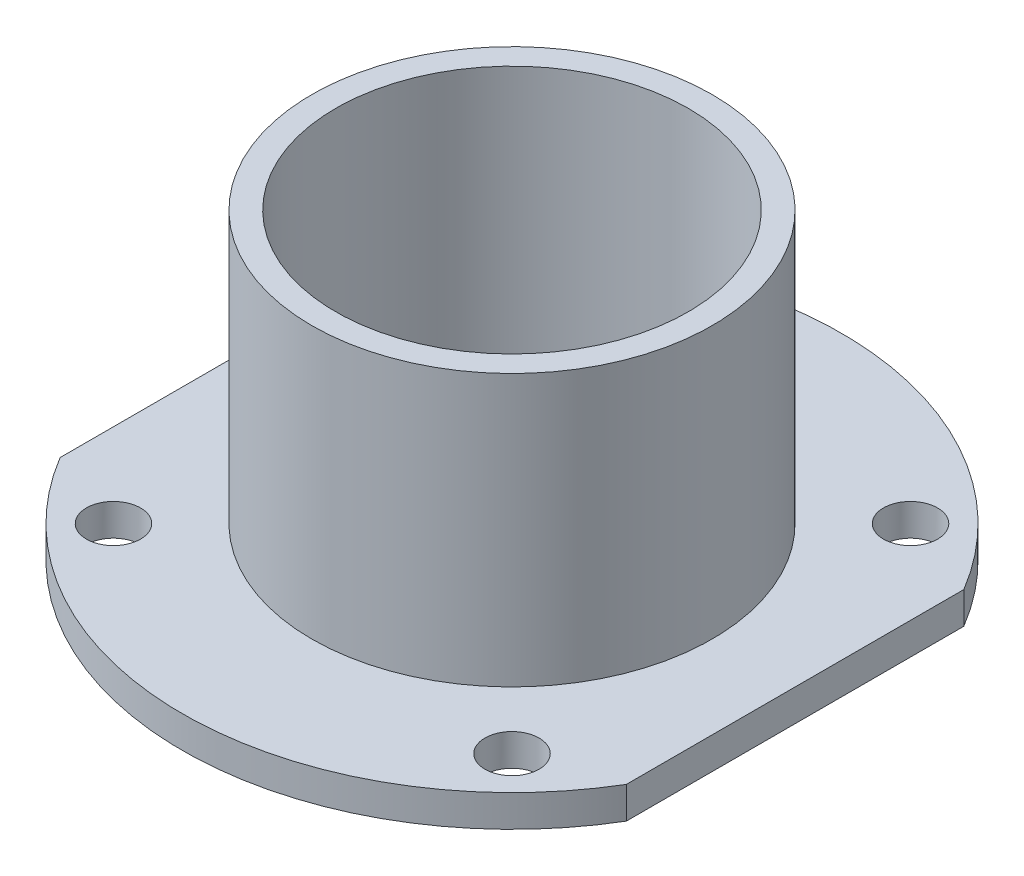
SolidWorks part; units mm, degrees
material "6061-T6 (SS)"
ref_plane "Front Plane" through (0, 0, 0) normal (0, 0, 1) x (1, 0, 0)
ref_plane "Top Plane" through (0, 0, 0) normal (0, 1, 0) x (1, 0, 0)
ref_plane "Right Plane" through (0, 0, 0) normal (1, 0, 0) x (0, 0, -1)
sketch "Sketch1" plane through (0, 0, 0) normal (0, 0, 1) x (1, 0, 0)
  line L0 (12.573, 2) -> (20.7, 2)
  line L2 (11.073, 0) -> (11.073, 19.05)
  line L3 (11.073, 19.05) -> (12.573, 19.05)
  line L4 (12.573, 19.05) -> (12.573, 2)
  line L6 (20.7, 2) -> (20.7, 0)
  line L7 (20.7, 0) -> (11.073, 0)
  line L8 (0, 0) -> (0, 19.05) construction
  dimension "D1" = 2
  dimension "D2" = 19.05
  dimension "D3" = 20.7
  dimension "D4" = 1.5
  dimension "D5" = 25.146
revolve "Revolve1" add sketch "Sketch1" angle 360 about L8
sketch "Sketch2" plane through (0, 2, 0) normal (0, 1, 0) x (1, 0, 0)
  line L0 (-12.5158, 12.5158) -> (-12.5158, -12.5158) construction
  line L1 (-12.5158, -12.5158) -> (12.5158, -12.5158) construction
  line L2 (12.5158, -12.5158) -> (12.5158, 12.5158) construction
  line L3 (12.5158, 12.5158) -> (-12.5158, 12.5158) construction
  line L4 (0, 0) -> (29.0927, 0) construction
  line L5 (0, 0) -> (-27.6955, 0) construction
  line L6 (-27.6955, 10.9507) -> (-27.6955, -10.9507) construction
  line L7 (29.0927, 10.9507) -> (29.0927, -10.9507) construction
  circle A0 centre (0, 0) radius 17.7 construction
  circle A2 centre (0, 0) radius 20.7 construction
  dimension "D1" = 3
sketch "Sketch3" plane through (0, 0, 0) normal (0, -1, 0) x (1, 0, 0)
  line L0 (-17.78, 10.6001) -> (-17.78, -10.6001)
  line L2 (17.78, -10.6001) -> (17.78, 10.6001)
  circle A0 centre (0, 0) radius 20.7 construction
  arc A1 (-17.78, 10.6001) -> (-17.78, -10.6001) centre (0, 0) ccw
  arc A2 (17.78, 10.6001) -> (17.78, -10.6001) centre (0, 0) cw
  dimension "D1" = 35.56
extrude "Cut-Extrude2" cut sketch "Sketch3" against normal through all
hole_wizard "M3 Clearance Hole1" positions "3DSketch1" profile "Sketch4" hole size "M3" standard "ANSI Metric"
sketch3d "3DSketch1"
  point P0 (12.5158, 2, 12.5158)
  point P3 (-12.5158, 2, 12.5158)
  point P6 (-12.5158, 2, -12.5158)
  point P9 (12.5158, 2, -12.5158)
sketch "Sketch4" plane through (12.5158, 2, 12.5158) normal (1, 0, 0) x (0, 0, 1)
  line L0 (0, 0) -> (0, 12.7)
  line L1 (0, 12.7) -> (1.7, 12.7)
  line L2 (1.7, 12.7) -> (1.7, 0)
  line L5 (1.7, 0) -> (0, 0)
  line L10 (0, 12.7) -> (-1.7, 12.7) construction
  line L11 (0, -6.35) -> (0, 107.95) construction
  dimension "Hole Dia." = 3.4
  dimension "Hole Depth" = 12.7
  dimension "Drill Angle" = 180
